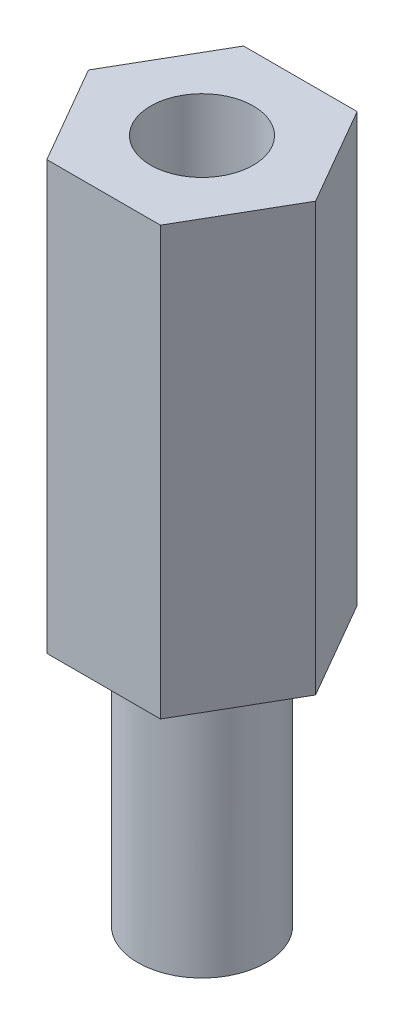
SolidWorks part; units mm, degrees
other "Markup1"
sketch "Sketch2" plane through (2.6558, 40, 2.3) normal (0.3825, 0.9065, 0.1787) x (0.7461, -0.1889, -0.6385)
ref_plane "Front Plane" through (0, 0, 0) normal (0, 0, 1) x (1, 0, 0)
ref_plane "Top Plane" through (0, 0, 0) normal (0, 1, 0) x (1, 0, 0)
ref_plane "Right Plane" through (0, 0, 0) normal (1, 0, 0) x (0, 0, -1)
sketch "Sketch1" plane through (0, 0, 0) normal (0, 1, 0) x (1, 0, 0)
  line L1 (2.6558, 0) -> (1.3279, 2.3)
  line L2 (1.3279, 2.3) -> (-1.3279, 2.3)
  line L3 (-1.3279, 2.3) -> (-2.6558, 0)
  line L4 (-2.6558, 0) -> (-1.3279, -2.3)
  line L5 (-1.3279, -2.3) -> (1.3279, -2.3)
  line L6 (1.3279, -2.3) -> (2.6558, 0)
  circle A0 centre (0, 0) radius 2.3 construction
  circle A2 centre (0, 0) radius 1.2
  dimension "D2" = 1.2
  dimension "D1" = 4.6
extrude "Boss-Extrude1" add sketch "Sketch1" along normal blind 10
sketch "Sketch3" plane through (0, 0, 0) normal (0, -1, 0) x (-1, 0, 0)
  circle A0 centre (0, 0) radius 1.5
  dimension "D1" = 3
extrude "Boss-Extrude2" add sketch "Sketch3" along normal blind 6
